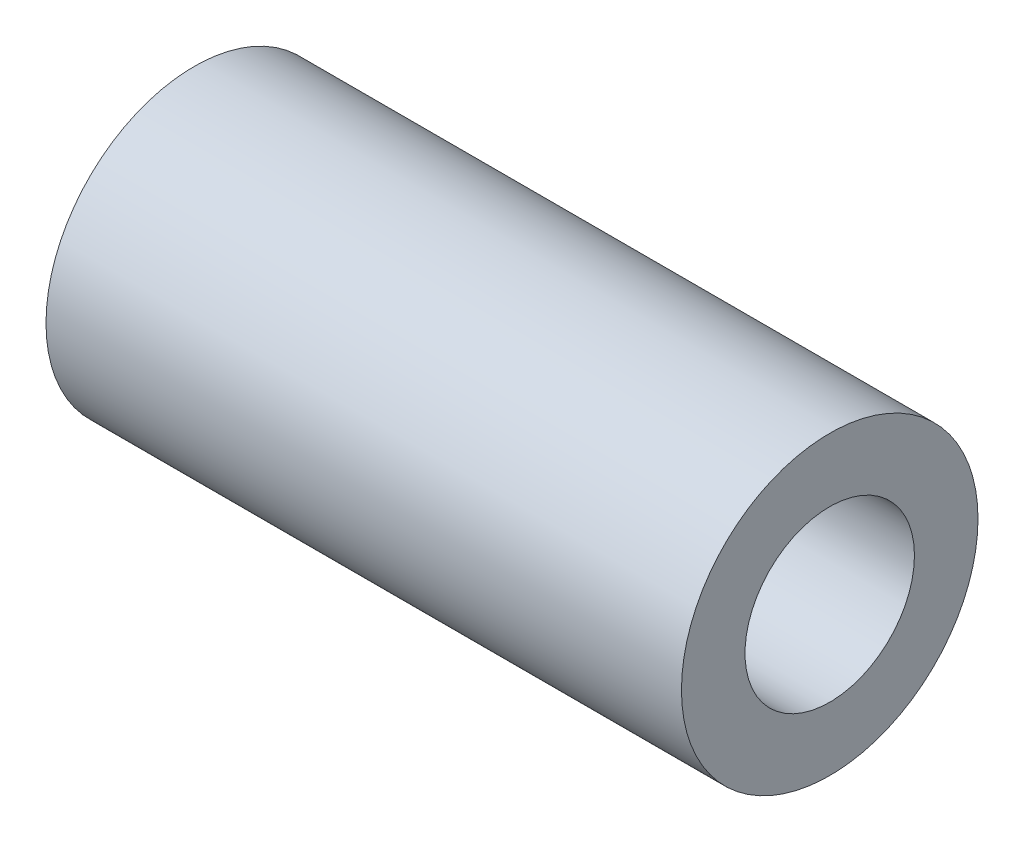
SolidWorks part; units mm, degrees
material "1060 合金"
ref_plane "前视基准面" through (0, 0, 0) normal (0, 0, 1) x (1, 0, 0)
ref_plane "上视基准面" through (0, 0, 0) normal (0, 1, 0) x (1, 0, 0)
ref_plane "右视基准面" through (0, 0, 0) normal (1, 0, 0) x (0, 0, -1)
other "Configuration Table"
sketch "草图1" plane through (0, 0, 0) normal (1, 0, 0) x (0, 0, -1)
  circle A0 centre (0, 0) radius 2
  circle A1 centre (0, 0) radius 3.5
  dimension "D1" = 4
  dimension "D2" = 7
extrude "凸台-拉伸1" add sketch "草图1" along normal mid plane 15
